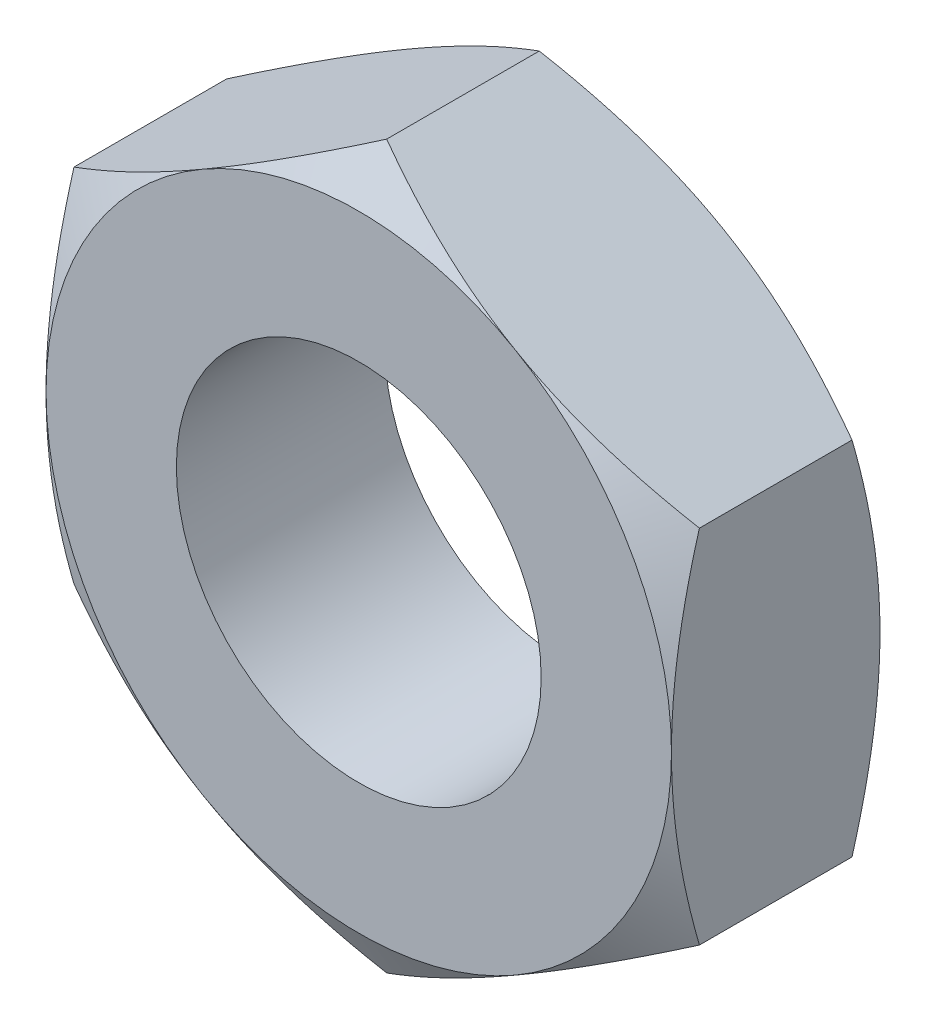
SolidWorks part; units mm, degrees
material "1.4000 (X6Cr13)"
ref_plane "Płaszczyzna przednia" through (0, 0, 0) normal (0, 0, 1) x (1, 0, 0)
ref_plane "Płaszczyzna górna" through (0, 0, 0) normal (0, 1, 0) x (1, 0, 0)
ref_plane "Płaszczyzna prawa" through (0, 0, 0) normal (1, 0, 0) x (0, 0, -1)
sketch "Szkic1" plane through (0, 0, 0) normal (0, 0, 1) x (1, 0, 0)
  line L1 (-3, 1.7321) -> (-3, -1.7321)
  line L2 (-3, -1.7321) -> (0, -3.4641)
  line L3 (0, -3.4641) -> (3, -1.7321)
  line L4 (3, -1.7321) -> (3, 1.7321)
  line L5 (3, 1.7321) -> (0, 3.4641)
  line L6 (0, 3.4641) -> (-3, 1.7321)
  circle A0 centre (0, 0) radius 1.75
  circle A1 centre (0, 0) radius 3 construction
  dimension "d" = 3.5
  dimension "s" = 6
extrude "Dodanie-wyciągnięcie1" add sketch "Szkic1" along normal mid plane 2
sketch "Szkic2" plane through (0, 0, 1) normal (0, 0, 1) x (1, 0, 0)
  circle A0 centre (0, 0) radius 3
  dimension "D1" = 6
extrude "Wytnij-wyciągnięcie2" cut sketch "Szkic2" against normal blind 2 draft 60 flip side to cut
mirror "Lustro1" about plane through (0, 0, 0) normal (0, 0, 1) of "Wytnij-wyciągnięcie2"
equation "\"D1@Szkic2\" = \"s@Szkic1\""
equation "\"D1@Wytnij-wyciągnięcie2\" = \"m@Dodanie-wyciągnięcie1\""
